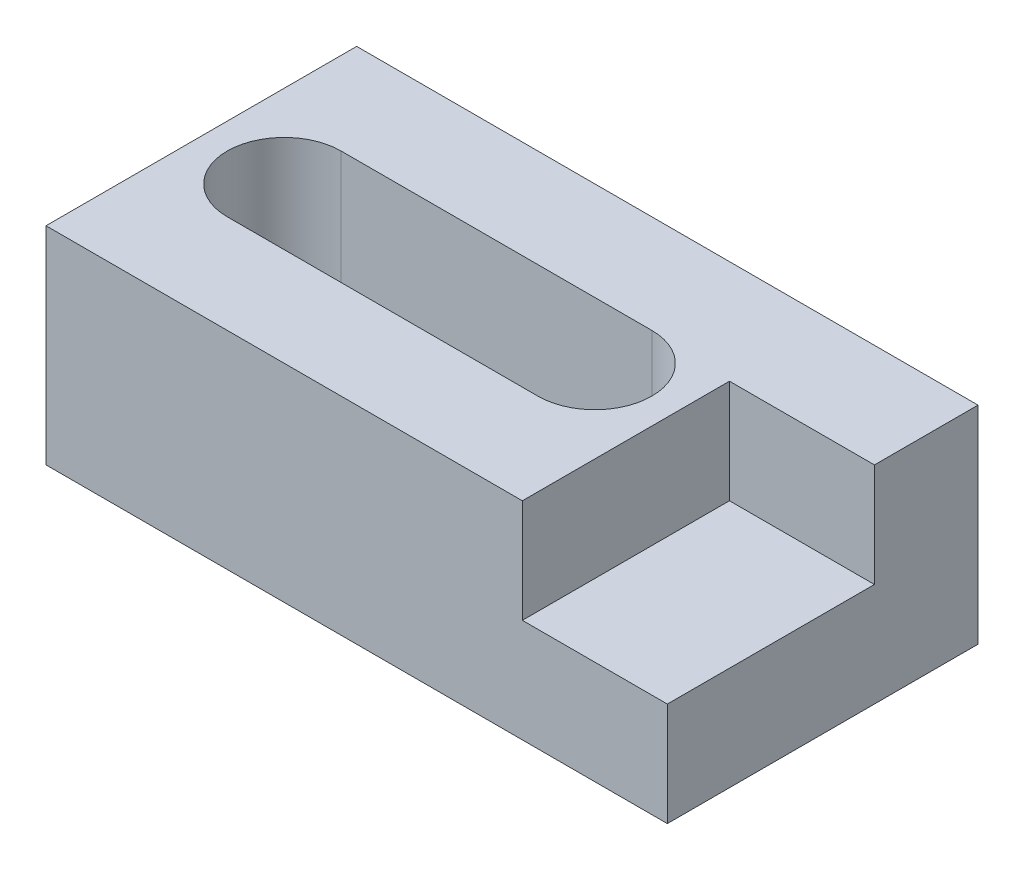
SolidWorks part; units mm, degrees
ref_plane "Front Plane" through (0, 0, 0) normal (0, 0, 1) x (1, 0, 0)
ref_plane "Top Plane" through (0, 0, 0) normal (0, 1, 0) x (1, 0, 0)
ref_plane "Right Plane" through (0, 0, 0) normal (1, 0, 0) x (0, 0, -1)
sketch "Sketch1" plane through (0, 0, 0) normal (0, 1, 0) x (1, 0, 0)
  line L0 (15, 0) -> (-15, 0) construction
  line L1 (-15, -7.5) -> (15, -7.5)
  line L2 (-15, -7.5) -> (-15, 7.5)
  line L3 (-15, 7.5) -> (15, 7.5)
  line L4 (15, -7.5) -> (15, 7.5)
  line L5 (-15, -7.5) -> (15, 7.5) construction
  line L6 (-15, 7.5) -> (15, -7.5) construction
  line L10 (7.5, 7.5) -> (7.5, -7.5) construction
  line L11 (-11, 2.75) -> (4, 2.75)
  line L12 (-11, -2.75) -> (4, -2.75)
  arc A0 (-11, 2.75) -> (-11, -2.75) centre (-11, 0) ccw
  arc A2 (4, -2.75) -> (4, 2.75) centre (4, 0) ccw
  point P0 (0, 0)
  dimension "D6" = 5.5
  dimension "D1" = 15
  dimension "D2" = 7.5
  dimension "D3" = 30
  dimension "D4" = 15
  dimension "D5" = 4
extrude "Boss-Extrude1" add sketch "Sketch1" along normal blind 10
sketch "Sketch2" plane through (0, 0, 7.5) normal (0, 0, 1) x (1, 0, 0)
  line L1 (15, 10) -> (8, 10)
  line L2 (15, 10) -> (15, 5)
  line L3 (15, 5) -> (8, 5)
  line L4 (8, 10) -> (8, 5)
  dimension "D1" = 7
  dimension "D2" = 5
extrude "Cut-Extrude1" cut sketch "Sketch2" against normal through all both and the other way through all
sketch "Sketch3" plane through (0, 5, 0) normal (0, 1, 0) x (1, 0, 0)
  line L0 (8, 7.5) -> (8, -7.5) construction
  line L1 (15, 7.5) -> (8, 7.5)
  line L2 (15, 7.5) -> (15, 2.5)
  line L3 (15, 2.5) -> (8, 2.5)
  line L4 (8, 7.5) -> (8, 2.5)
  dimension "D1" = 5
extrude "Boss-Extrude2" add sketch "Sketch3" along normal up to surface (5 mm away) up to face at (-3.5, 10, 0)
